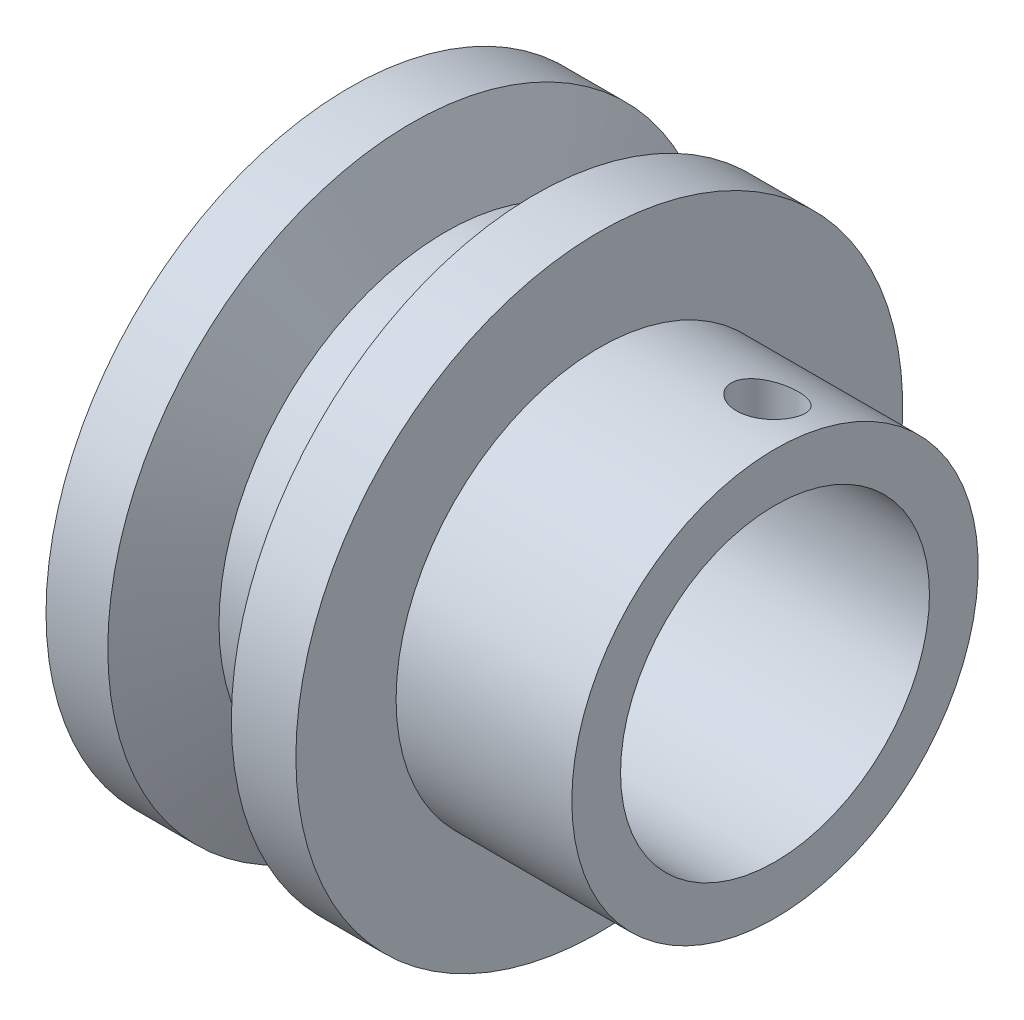
SolidWorks part; units mm, degrees
ref_plane "Front Plane" through (0, 0, 0) normal (0, 0, 1) x (1, 0, 0)
ref_plane "Top Plane" through (0, 0, 0) normal (0, 1, 0) x (1, 0, 0)
ref_plane "Right Plane" through (0, 0, 0) normal (1, 0, 0) x (0, 0, -1)
sketch "Sketch1" plane through (0, 0, 0) normal (0, 0, 1) x (1, 0, 0)
  line L0 (-184.466, 0) -> (162.8674, 0) construction
  line L1 (-142.466, 147.3333) -> (-142.466, 0)
  line L2 (-142.466, 147.3333) -> (-112.466, 147.3333)
  line L3 (-112.466, 147.3333) -> (-95.7993, 110)
  line L4 (-95.7993, 110) -> (-75.7993, 110)
  line L5 (-75.7993, 110) -> (-52.466, 147.3333)
  line L6 (-52.466, 147.3333) -> (-21.1326, 147.3333)
  line L7 (-21.1326, 147.3333) -> (-21.1326, 98.6667)
  line L8 (-21.1326, 98.6667) -> (64.2007, 98.6667)
  line L9 (64.2007, 98.6667) -> (64.2007, 0)
  line L10 (64.2007, 73.6667) -> (-137.466, 73.6667)
  line L11 (-137.466, 73.6667) -> (-137.466, 0)
  line L12 (-142.466, 0) -> (-137.466, 0)
  line L13 (-137.466, 0) -> (64.2007, 0)
  point P16 (-64.1326, 128.6667)
  point P17 (-104.1326, 128.6667)
  dimension "D1" = 20
  dimension "D2" = 40
  dimension "D3" = 5
  dimension "D4" = 25
  dimension "D5" = 201.6667
revolve "Revolve4" add sketch "Sketch1" angle 360 about L0
sketch "Sketch9" plane through (-142.466, 0, 0) normal (-1, 0, 0) x (0, 0, 1)
  circle A0 centre (0, 0) radius 75
  dimension "D1" = 150
extrude "Cut-Extrude1" cut sketch "Sketch9" against normal through all contours A0
ref_plane "Plane4" through (0, 25, 0) normal (0, 1, 0) x (1, 0, 0)
sketch "Sketch14" plane through (0, 25, 0) normal (0, 1, 0) x (1, 0, 0)
  line L0 (64.2007, -98.6667) -> (64.2007, 98.6667) construction
  circle A1 centre (38.6286, 21.9145) radius 15
  dimension "D1" = 30
  dimension "D2" = 25.5721
extrude "Cut-Extrude4" cut sketch "Sketch14" along normal through all
